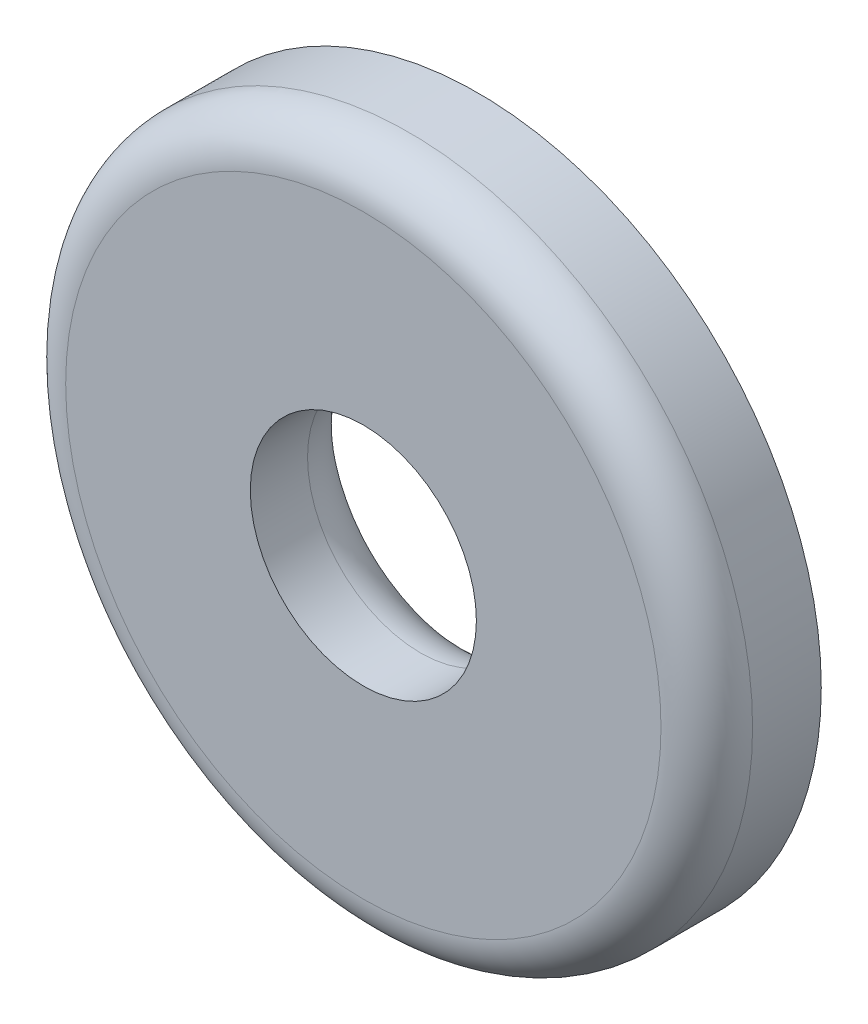
SolidWorks part; units mm, degrees
ref_plane "Top" through (0, 0, 0) normal (0, 0, 1) x (1, 0, 0)
ref_plane "Front" through (0, 0, 0) normal (0, 1, 0) x (1, 0, 0)
ref_plane "Right" through (0, 0, 0) normal (1, 0, 0) x (0, 0, -1)
sketch "Sketch10" plane through (0, 0, 0) normal (0, 0, 1) x (1, 0, 0)
  line L0 (50, 0) -> (-50, 0) construction
  circle A0 centre (-81.433, 0) radius 9.875
  circle A1 centre (-81.433, 0) radius 30
  dimension "D1" = 19.75
  dimension "D2" = 60
extrude "Boss-Extrude4" add sketch "Sketch10" along normal blind 10 separate body
fillet "Fillet1" radius 4 1 edges at (-51.433, 0, 10)
fillet "Fillet2" radius 5 1 edges at (-71.558, 0, 0)
